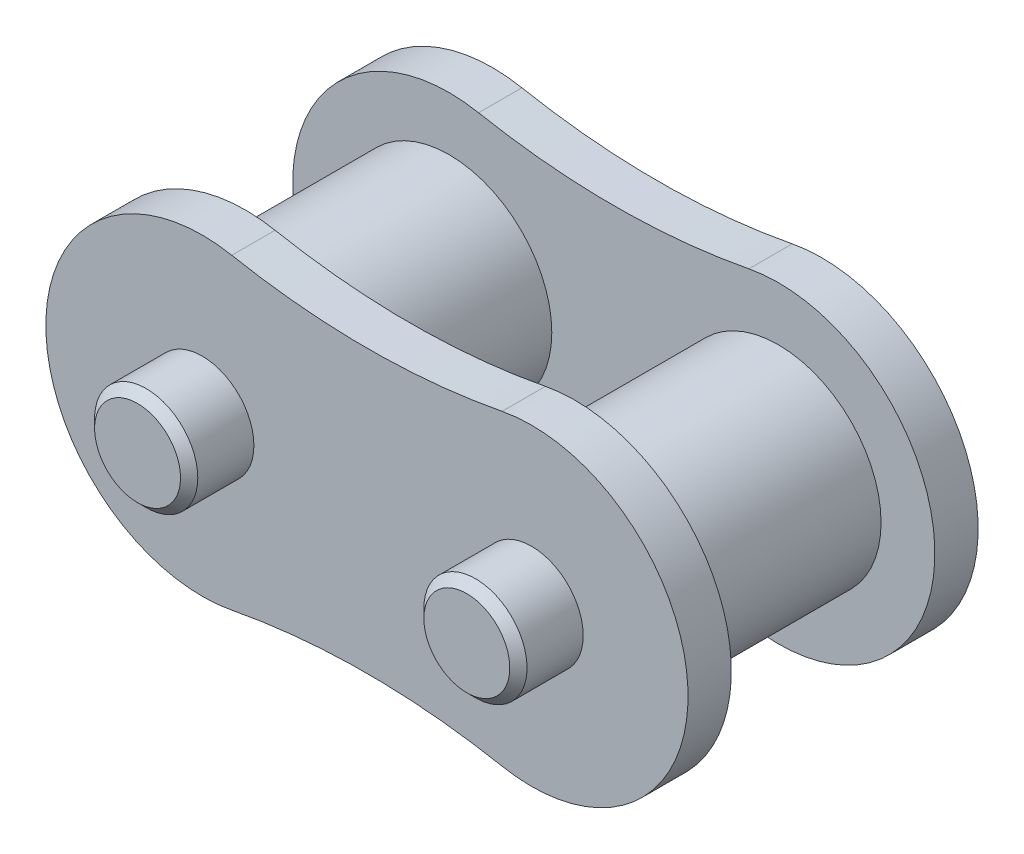
SolidWorks part; units mm, degrees
ref_plane "前视基准面" through (0, 0, 0) normal (0, 0, 1) x (1, 0, 0)
ref_plane "上视基准面" through (0, 0, 0) normal (0, 1, 0) x (1, 0, 0)
ref_plane "右视基准面" through (0, 0, 0) normal (1, 0, 0) x (0, 0, -1)
sketch "草图1" plane through (0, 0, 0) normal (0, 0, 1) x (1, 0, 0)
  line L0 (-6.35, 0) -> (6.35, 0) construction
  line L1 (0, 5.4315) -> (0, -5.4315) construction
  line L2 (6.35, 0) -> (17.53, 0) construction
  line L3 (17.53, 0) -> (25.38, 0) construction
  circle A0 centre (-6.35, 0) radius 6.035
  circle A1 centre (6.35, 0) radius 6.035
  circle A2 centre (0, 33.1055) radius 27.674
  circle A3 centre (0, -33.1055) radius 27.674
  circle A4 centre (-6.35, 0) radius 3.96
  circle A5 centre (6.35, 0) radius 3.96
  circle A6 centre (-6.35, 0) radius 1.99
  circle A7 centre (6.35, 0) radius 1.99
  dimension "h2" = 12.07
  dimension "d1" = 7.92
  dimension "d2" = 3.98
  dimension "p" = 12.7
  dimension "h3" = 10.863
  dimension "b2" = 11.18
  dimension "b1" = 7.85
sketch "草图2" plane through (0, 0, 0) normal (0, 0, 1) x (1, 0, 0)
  circle A0 centre (6.35, 0) radius 3.96 construction
  circle A1 centre (-6.35, 0) radius 3.96 construction
  circle A2 centre (6.35, 0) radius 3.96
  circle A3 centre (-6.35, 0) radius 3.96
extrude "拉伸1" add sketch "草图2" along normal mid plane 7.85
sketch "草图3" plane through (0, 0, 3.925) normal (0, 0, 1) x (1, 0, 0)
  circle A0 centre (-6.35, 0) radius 6.035 construction
  arc A1 (-5.2131, 5.927) -> (-5.2131, -5.927) centre (-6.35, 0) ccw
  circle A2 centre (6.35, 0) radius 6.035 construction
  arc A3 (5.2131, -5.927) -> (5.2131, 5.927) centre (6.35, 0) ccw
  circle A4 centre (0, 33.1055) radius 27.674 construction
  arc A5 (-5.2131, 5.927) -> (5.2131, 5.927) centre (0, 33.1055) ccw
  circle A6 centre (0, -33.1055) radius 27.674 construction
  arc A7 (5.2131, -5.927) -> (-5.2131, -5.927) centre (0, -33.1055) ccw
extrude "拉伸2" add sketch "草图3" along normal blind 1.67
sketch "草图4" plane through (0, 0, 5.595) normal (0, 0, 1) x (1, 0, 0)
  circle A0 centre (6.35, 0) radius 1.99 construction
  circle A1 centre (-6.35, 0) radius 1.99 construction
  circle A2 centre (6.35, 0) radius 1.99
  circle A3 centre (-6.35, 0) radius 1.99
extrude "拉伸3" add sketch "草图4" along normal blind 2.4975
chamfer "倒角1" distance 0.333 angle 45 2 edges at (8.34, 0, 8.0925) (-4.36, 0, 8.0925)
mirror "镜向1" about plane through (0, 0, 0) normal (0, 0, 1) of "拉伸2", "倒角1", "拉伸3"
ref_point "点2"
ref_point "点6"
sketch "草图5" plane through (0, 0, 0) normal (0, 0, 1) x (1, 0, 0)
  line L0 (-6.35, 0) -> (6.35, 0)
equation "\"D1@拉伸2\"= ( \"b2@草图1\" - 7.85 ) / 2"
equation "\"D1@拉伸3\" = \"D1@拉伸2\" * 1.5"
equation "\"D1@倒角1\" = \"D1@拉伸2\" / 5"
equation "\"D1@拉伸1\" = \"b1@草图1\""
equation "\"h3@草图1\" = \"h2@草图1\" * 0.9"
